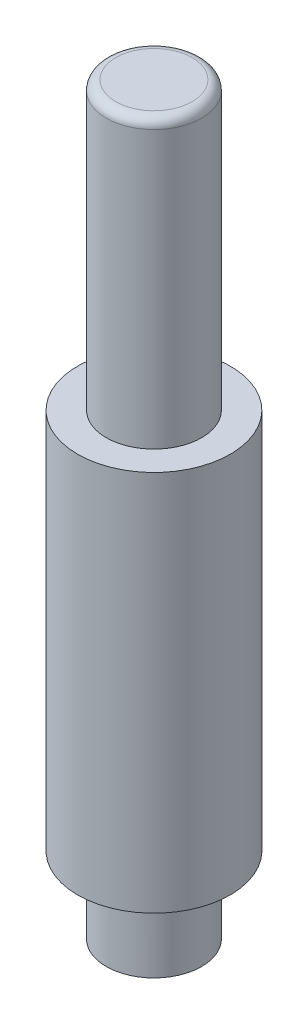
SolidWorks part; units mm, degrees
ref_plane "Front Plane" through (0, 0, 0) normal (0, 0, 1) x (1, 0, 0)
ref_plane "Top Plane" through (0, 0, 0) normal (0, 1, 0) x (1, 0, 0)
ref_plane "Right Plane" through (0, 0, 0) normal (1, 0, 0) x (0, 0, -1)
sketch "Sketch9" plane through (0, 0, 0) normal (0, 1, 0) x (1, 0, 0)
  circle A0 centre (0, 0) radius 5
  dimension "D1" = 10
extrude "Boss-Extrude7" add sketch "Sketch9" along normal blind 7.5
sketch "Sketch10" plane through (0, 7.5, 0) normal (0, 1, 0) x (1, 0, 0)
  circle A0 centre (0, 0) radius 4.5
extrude "Boss-Extrude8" add sketch "Sketch10" along normal blind 0.5
sketch "Sketch11" plane through (0, 8, 0) normal (0, 1, 0) x (1, 0, 0)
  circle A1 centre (0, 0) radius 8
extrude "Boss-Extrude9" add sketch "Sketch11" along normal blind 40
sketch "Sketch12" plane through (0, 48, 0) normal (0, 1, 0) x (1, 0, 0)
  circle A0 centre (0, 0) radius 5
  dimension "D1" = 10
extrude "Boss-Extrude10" add sketch "Sketch12" along normal blind 30
fillet "Fillet7" radius 1 1 edges at (0, 78, 5)
hole_wizard "CBORE for M6 Hex Head Bolt2" positions "Sketch25" profile "Sketch26" counterbore size "M6" standard "ISO"
sketch "Sketch25" plane through (0, 0, 0) normal (0, -1, 0) x (-1, 0, 0)
  point P0 (0, 0)
sketch "Sketch26" plane through (0, 0, 0) normal (1, 0, 0) x (0, 0, -1)
  line L0 (0, 0) -> (0, 11.9828)
  line L1 (0, 11.9828) -> (3.3, 10)
  line L2 (3.3, 10) -> (3.3, 4)
  line L3 (3.3, 4) -> (7.2735, 4)
  line L4 (7.2735, 4) -> (7.2735, 0)
  line L5 (7.2735, 0) -> (0, 0)
  line L10 (0, 11.9828) -> (-3.3, 10) construction
  line L11 (0, -6.35) -> (0, 107.95) construction
  dimension "Hole Dia." = 6.6
  dimension "Hole Depth" = 10
  dimension "C'Bore Dia." = 14.547
  dimension "C'Bore Depth" = 4
  dimension "Drill Angle" = 118
sketch "Sketch27" plane through (0, 4, 0) normal (0, -1, 0) x (1, 0, 0)
  circle A0 centre (0, 0) radius 5
extrude "Boss-Extrude11" add sketch "Sketch27" along normal blind 4
sketch "Sketch28" plane through (0, 0, 0) normal (0, -1, 0) x (1, 0, 0)
  circle A0 centre (0, 0) radius 3.3
extrude "Cut-Extrude1" cut sketch "Sketch28" against normal blind 5
